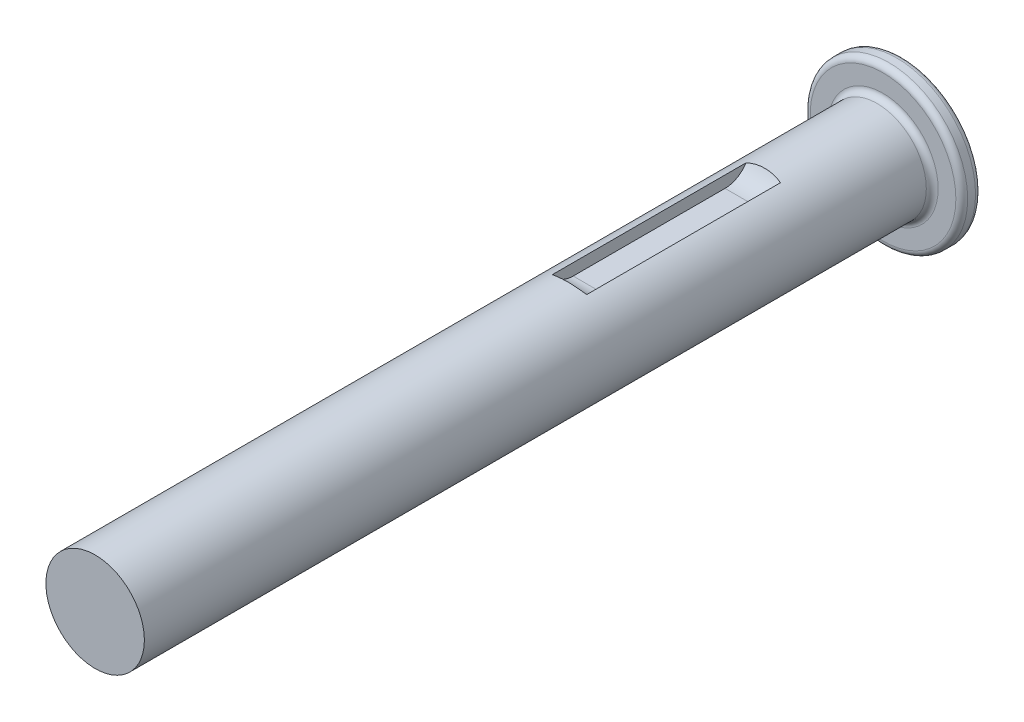
SolidWorks part; units mm, degrees
ref_plane "Front Plane" through (0, 0, 0) normal (0, 0, 1) x (1, 0, 0)
ref_plane "Top Plane" through (0, 0, 0) normal (0, 1, 0) x (1, 0, 0)
ref_plane "Right Plane" through (0, 0, 0) normal (1, 0, 0) x (0, 0, -1)
sketch "Sketch1" plane through (0, 0, 0) normal (0, 0, 1) x (1, 0, 0)
  circle A0 centre (0, 0) radius 8
  dimension "D1" = 16
extrude "Boss-Extrude1" add sketch "Sketch1" along normal blind 2
sketch "Sketch2" plane through (0, 0, 2) normal (0, 0, 1) x (1, 0, 0)
  circle A0 centre (0, 0) radius 5
  dimension "D1" = 10
extrude "Boss-Extrude2" add sketch "Sketch2" along normal blind 80
sketch "Sketch4" plane through (0, 0, 0) normal (1, 0, 0) x (0, 0, -1)
  line L0 (-2, 5) -> (-82, 5) construction
  line L1 (-2, 8) -> (-2, -8) construction
  line L2 (-34, 5) -> (-14, 5)
  line L3 (-31.7087, 3.5) -> (-16.2913, 3.5)
  arc A2 (-34, 5) -> (-31.7087, 3.5) centre (-31.7087, 6) ccw
  arc A3 (-16.2913, 3.5) -> (-14, 5) centre (-16.2913, 6) ccw
  point P0 (-10, 5)
  point P1 (-46, 5)
  point P6 (-14, 5)
  point P7 (-34, 5)
  point P9 (-38, 5)
  dimension "D7" = 5
  dimension "D1" = 8
  dimension "D2" = 20
  dimension "D3" = 44
  dimension "D4" = 8
  dimension "D6" = 4
extrude "Cut-Extrude1" cut sketch "Sketch4" against normal mid plane 3.5
fillet "Fillet2" radius 0.6 3 edges at (8, 0, 0) (8, 0, 2) (5, 0, 2)
